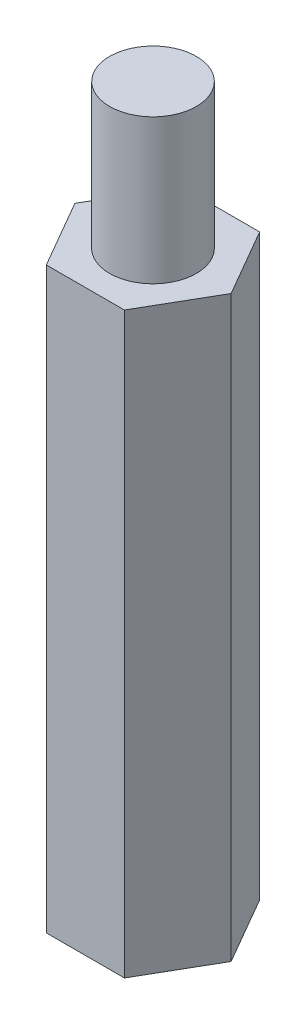
SolidWorks part; units mm, degrees
material "黄铜"
ref_plane "前视基准面" through (0, 0, 0) normal (0, 0, 1) x (1, 0, 0)
ref_plane "上视基准面" through (0, 0, 0) normal (0, 1, 0) x (1, 0, 0)
ref_plane "右视基准面" through (0, 0, 0) normal (1, 0, 0) x (0, 0, -1)
other "Configuration Table"
sketch "草图1" plane through (0, 0, 0) normal (0, 1, 0) x (1, 0, 0)
  line L4 (2.7, 0) -> (1.35, 2.3383)
  line L5 (1.35, 2.3383) -> (-1.35, 2.3383)
  line L6 (-1.35, 2.3383) -> (-2.7, 0)
  line L7 (-2.7, 0) -> (-1.35, -2.3383)
  line L8 (-1.35, -2.3383) -> (1.35, -2.3383)
  line L9 (1.35, -2.3383) -> (2.7, 0)
  circle A0 centre (0, 0) radius 2.3383 construction
  dimension "D1" = 2.7
extrude "凸台-拉伸1" add sketch "草图1" along normal blind 20
sketch "草图2" plane through (0, 0, 0) normal (0, 1, 0) x (1, 0, 0)
  circle A0 centre (0, 0) radius 1.5
extrude "凸台-拉伸2" add sketch "草图2" along normal blind 25
sketch "草图3" plane through (0, 0, 0) normal (0, 1, 0) x (1, 0, 0)
  circle A0 centre (0, 0) radius 1.5
extrude "切除-拉伸2" cut sketch "草图3" against normal blind 1 and the other way blind 5 contours A0
